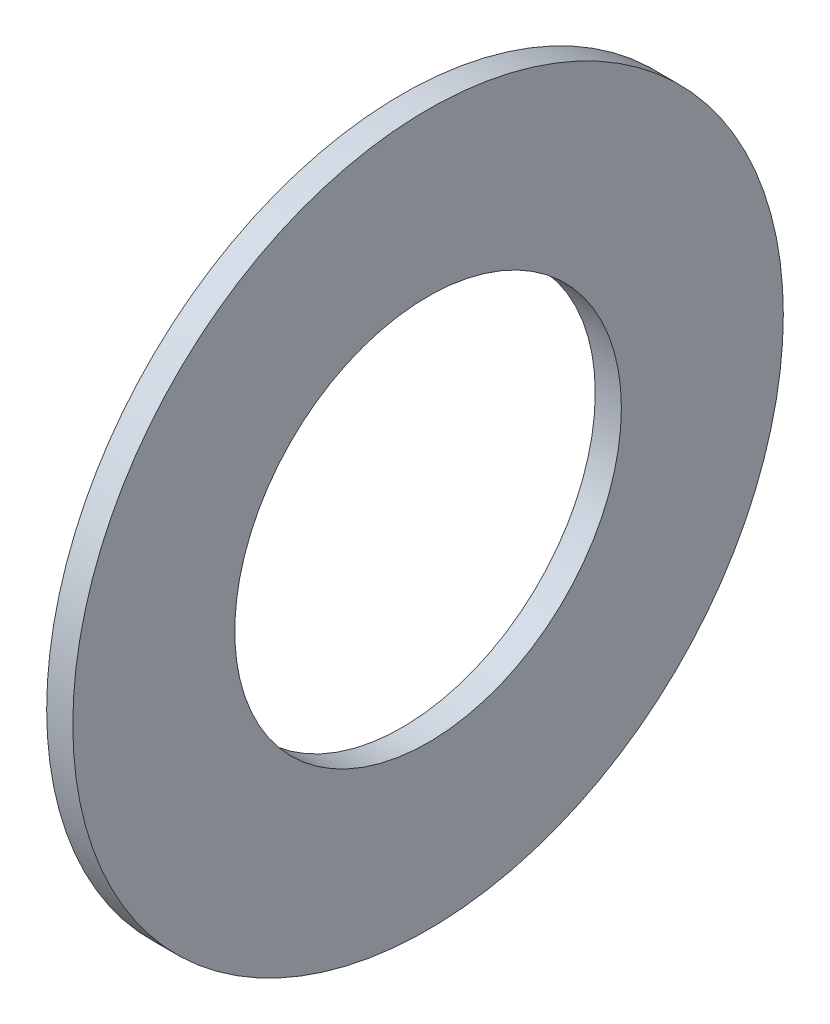
SolidWorks part; units mm, degrees
ref_plane "Plane1" through (0, 0, 0) normal (0, 0, 1) x (1, 0, 0)
ref_plane "Plane2" through (0, 0, 0) normal (0, 1, 0) x (1, 0, 0)
ref_plane "Plane3" through (0, 0, 0) normal (1, 0, 0) x (0, 0, -1)
sketch "Sketch1" plane through (0, 0, 0) normal (1, 0, 0) x (0, 0, -1)
  circle A0 centre (0, 0) radius 18.5
  circle A1 centre (0, 0) radius 34
  dimension "InsideDia" = 37
  dimension "OutsideDia" = 68
extrude "Base-Extrude" add sketch "Sketch1" along normal blind 2.5
